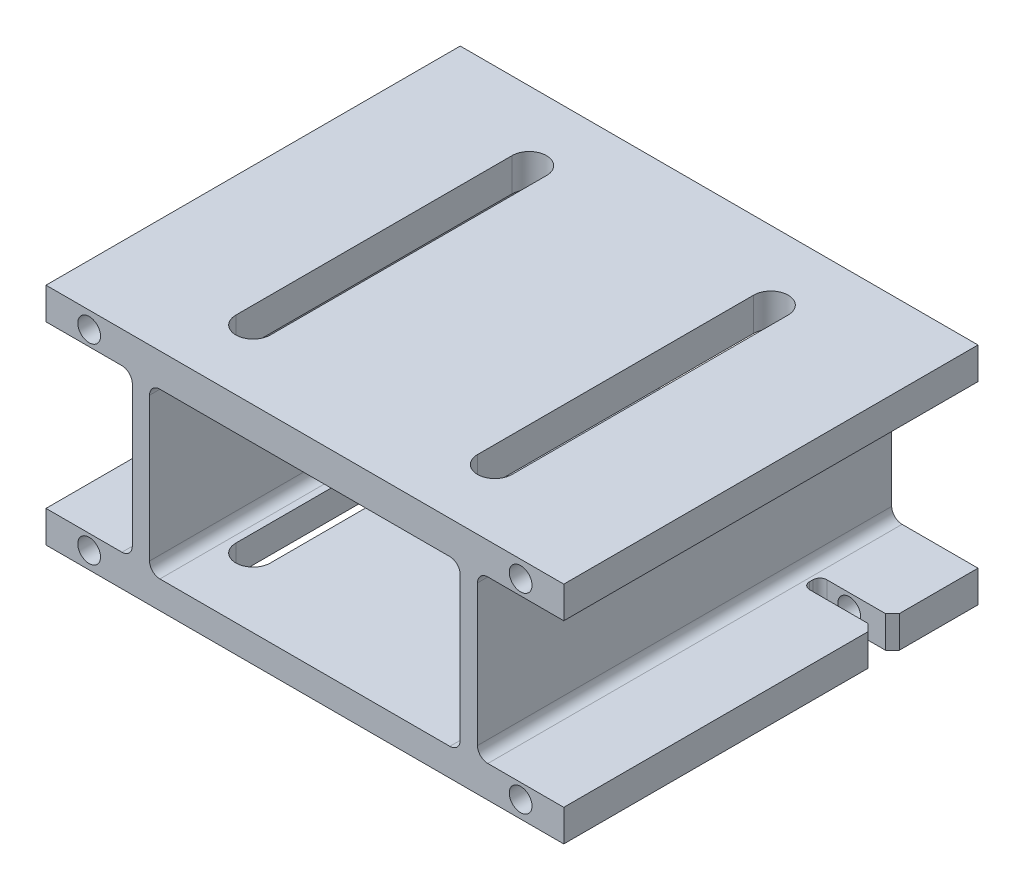
SolidWorks part; units mm, degrees
ref_plane "Front Plane" through (0, 0, 0) normal (0, 0, 1) x (1, 0, 0)
ref_plane "Top Plane" through (0, 0, 0) normal (0, 1, 0) x (1, 0, 0)
ref_plane "Right Plane" through (0, 0, 0) normal (1, 0, 0) x (0, 0, -1)
sketch "Sketch1" plane through (0, 0, 0) normal (0, 0, 1) x (1, 0, 0)
  line L0 (-25, 0) -> (25, 0)
  line L1 (-25, -11.7) -> (-25, 11.7)
  line L2 (-25, -16.3) -> (-25, 16.3)
  line L3 (-25, 16.3) -> (-37.5, 16.3)
  line L4 (-37.5, 16.3) -> (-37.5, -16.3) construction
  line L5 (-37.5, -16.3) -> (-25, -16.3)
  line L6 (-25, 11.7) -> (-37.5, 11.7)
  line L7 (-25, -11.7) -> (-37.5, -11.7)
  line L8 (-25, 0) -> (-37.5, 0) construction
  line L9 (-31.25, -13.85) -> (-31.25, 13.85) construction
  line L10 (0, -55) -> (0, 55) construction
  line L11 (25, 0) -> (37.5, 0) construction
  line L12 (31.25, -13.85) -> (31.25, 13.85) construction
  line L13 (25, -11.7) -> (37.5, -11.7)
  line L14 (25, 11.7) -> (37.5, 11.7)
  line L15 (37.5, -16.3) -> (25, -16.3)
  line L16 (37.5, 16.3) -> (37.5, -16.3) construction
  line L17 (25, 16.3) -> (37.5, 16.3)
  line L18 (25, -16.3) -> (25, 16.3)
  line L19 (25, -11.7) -> (25, 11.7)
  line L20 (-25, 16.3) -> (25, 16.3)
  line L21 (-25, -16.3) -> (25, -16.3)
  line L22 (-25, 11.5) -> (25, 11.5)
  line L23 (-25, -12.3) -> (25, -12.3)
  line L24 (-37.5, 16.3) -> (-37.5, 11.7)
  line L25 (-37.5, -11.7) -> (-37.5, -16.3)
  line L26 (37.5, 16.3) -> (37.5, 11.7)
  line L27 (37.5, -16.3) -> (37.5, -11.7)
  line L28 (-23.6435, -14.2) -> (-23.6435, -14.2)
  line L29 (-23.6435, -14.2) -> (-23.6435, -14.2)
  line L30 (-22.5, -14.2) -> (-23.6435, -14.2)
  line L31 (-22.5, -12.3) -> (-22.5, 11.5)
  line L32 (22.5, -16.3) -> (22.5, 16.3) construction
  line L33 (-23.6435, 14.2) -> (-23.6435, 14.2)
  line L34 (-23.6435, 14.2) -> (-23.6435, 14.2)
  line L35 (22.5, -12.3) -> (22.5, 11.5)
  line L36 (-22.5, -14.2) -> (-22.5, 14.2) construction
  line L37 (-22.5, 14.2) -> (-23.6435, 14.2) construction
  circle A0 centre (-31.25, 13.85) radius 1.65
  circle A1 centre (-31.25, -13.85) radius 1.65
  circle A2 centre (31.25, -13.85) radius 1.65
  circle A3 centre (31.25, 13.85) radius 1.65
  point P4 (0, 0)
  point P8 (-25, 0)
  point P11 (-25, 0)
  point P23 (-31.25, 0)
  point P41 (31.25, 0)
  point P42 (25, 0)
  point P43 (25, 0)
  point P57 (0, 0)
  dimension "D5" = 3.3
  dimension "D6" = 3.3
  dimension "D1" = 50
  dimension "D2" = 23.4
  dimension "D3" = 32.6
  dimension "D4" = 12.5
  dimension "D7" = 27.7
  dimension "D8" = 4.8
  dimension "D9" = 4
  dimension "D10" = 2.5
  dimension "D11" = 2.5
extrude "Boss-Extrude1" add sketch "Sketch1" along normal blind 60
fillet "Fillet1" radius 1.5 8 edges at (-22.5, -12.3, 30) (-22.5, 11.5, 30) (22.5, 11.5, 30) (22.5, -12.3, 30) (25, -11.7, 30) (25, 11.7, 30) (-25, -11.7, 30) (-25, 11.7, 30)
sketch "Sketch2" plane through (37.5, 0, 0) normal (1, 0, 0) x (0, 0, -1)
  line L0 (-12.4, -16.3) -> (-12.4, -11.7)
  line L1 (-60, -16.3) -> (0, -16.3) construction
  line L2 (0, -11.7) -> (-60, -11.7) construction
  line L3 (0, -16.3) -> (0, -11.7) construction
  line L4 (-14.9, -11.7) -> (-14.9, -16.3)
  line L5 (-60, -11.7) -> (0, -11.7) construction
  line L6 (-14.9, -11.7) -> (-12.4, -11.7)
  line L7 (-14.9, -16.3) -> (-12.4, -16.3)
  dimension "D1" = 12.4
  dimension "D2" = 2.5
extrude "Cut-Extrude1" cut sketch "Sketch2" against normal blind 10.5
fillet "Fillet2" radius 1 2 edges at (27, -14, 12.4) (27, -14, 14.9)
chamfer "Chamfer1" distance 1 angle 45 2 edges at (37.5, -14, 12.4) (37.5, -14, 14.9)
mirror "Mirror2" about plane through (0, 0, 0) normal (1, 0, 0) of "Cut-Extrude1", "Fillet2"
chamfer "Chamfer2" distance 1 angle 45 2 edges at (-37.5, -14, 12.4) (-37.5, -14, 14.9)
sketch "Sketch3" plane through (0, -16.3, 0) normal (0, -1, 0) x (1, 0, 0)
  line L0 (-17.5, 0) -> (17.5, 0)
  line L1 (-37.5, 0) -> (37.5, 0) construction
  line L2 (-17.5, 0) -> (-17.5, 60) construction
  line L3 (-37.5, 60) -> (37.5, 60) construction
  line L4 (-17.5, 50) -> (-17.5, 10) construction
  line L5 (-15, 50) -> (-15, 10)
  line L6 (-20, 50) -> (-20, 10)
  line L7 (0, 0) -> (0, 60) construction
  line L8 (0, 30) -> (-37.5, 30) construction
  line L9 (-37.5, 60) -> (-37.5, 15.9) construction
  line L10 (0, -17.93) -> (0, 17.93) construction
  line L11 (17.5, 50) -> (17.5, 10) construction
  line L12 (15, 50) -> (15, 10)
  line L13 (20, 50) -> (20, 10)
  arc A0 (-15, 50) -> (-20, 50) centre (-17.5, 50) ccw
  arc A1 (-20, 10) -> (-15, 10) centre (-17.5, 10) ccw
  arc A2 (15, 50) -> (20, 50) centre (17.5, 50) cw
  arc A3 (20, 10) -> (15, 10) centre (17.5, 10) cw
  point P6 (0, 0)
  point P12 (-17.5, 30)
  point P23 (0, 0)
  point P28 (17.5, 30)
  dimension "D1" = 35
  dimension "D2" = 40
  dimension "D3" = 5
extrude "Cut-Extrude2" cut sketch "Sketch3" against normal through all both and the other way through all contours L6 A1 L5 A0 | A3 L13 A2 L12
